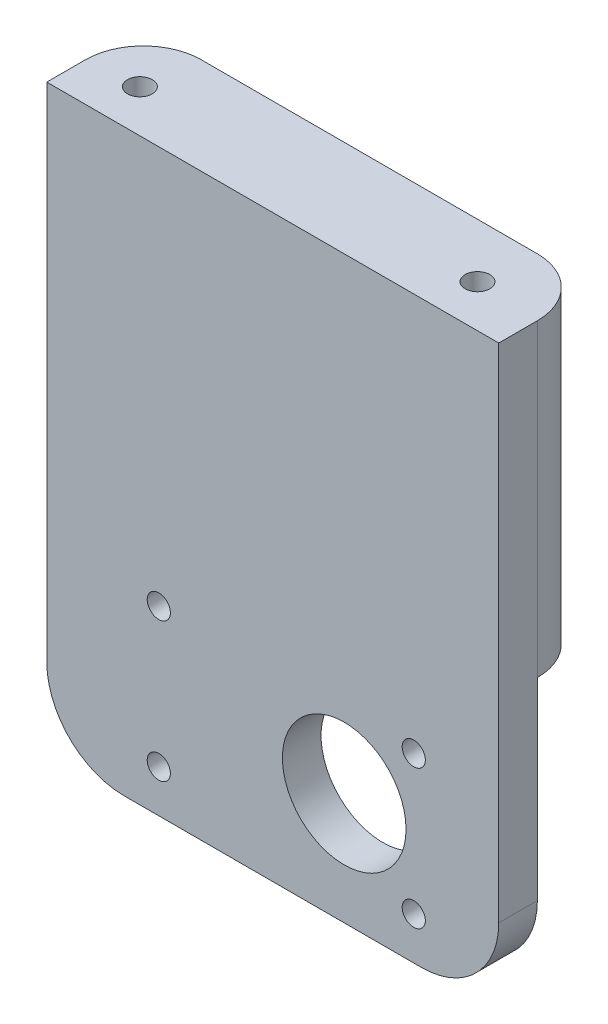
SolidWorks part; units mm, degrees
ref_plane "Front Plane" through (0, 0, 0) normal (0, 0, 1) x (1, 0, 0)
ref_plane "Top Plane" through (0, 0, 0) normal (0, 1, 0) x (1, 0, 0)
ref_plane "Right Plane" through (0, 0, 0) normal (1, 0, 0) x (0, 0, -1)
sketch "Sketch1" plane through (0, 0, 0) normal (0, 0, 1) x (1, 0, 0)
  line L5 (-24, 9) -> (9, 9) construction
  line L11 (-24, 9) -> (-24, -9) construction
  line L12 (-24, -9) -> (9, -9) construction
  line L13 (20, 60.5) -> (-38.5, 60.5)
  line L14 (20, 60.5) -> (20, -14.5)
  line L15 (20, -14.5) -> (-38.5, -14.5)
  line L16 (-38.5, 60.5) -> (-38.5, -14.5)
  line L17 (20, 60.5) -> (-38.5, -14.5) construction
  line L18 (20, -14.5) -> (-38.5, 60.5) construction
  line L23 (9, 9) -> (9, -9) construction
  line L25 (-24, 9) -> (9, -9) construction
  line L26 (-24, -9) -> (9, 9) construction
  circle A0 centre (0, 0) radius 8
  circle A1 centre (-24, -9) radius 1.5
  circle A2 centre (9, -9) radius 1.5
  circle A3 centre (9, 9) radius 1.5
  circle A4 centre (-24, 9) radius 1.5
  point P3 (-7.5, 0)
  point P9 (9, 0)
  point P10 (0, 0)
  point P11 (0, 0)
  dimension "D4" = 16
  dimension "D11" = 75
  dimension "D7" = 3
  dimension "D1" = 20
  dimension "D2" = 9
  dimension "D3" = 18
  dimension "D5" = 33
  dimension "D6" = 60.5
  dimension "D8" = 58.5
  dimension "D9" = 2
  dimension "D10" = 2
extrude "Boss-Extrude1" add sketch "Sketch1" along normal mid plane 5
sketch "Sketch4" plane through (0, 0, -2.5) normal (0, 0, -1) x (-1, 0, 0)
  line L0 (-20, 60.5) -> (-20, -14.5) construction
  line L1 (38.5, 60.5) -> (-20, 60.5)
  line L2 (38.5, 60.5) -> (38.5, 20.5)
  line L3 (38.5, 20.5) -> (-20, 20.5)
  line L4 (-20, 60.5) -> (-20, 20.5)
  dimension "D1" = 40
extrude "Boss-Extrude2" add sketch "Sketch4" along normal blind 7.5
hole_wizard "M3 Clearance Hole1" positions "Sketch2" profile "Sketch3" hole size "M3" standard "ISO"
sketch "Sketch2" plane through (0, 60.5, 0) normal (0, 1, 0) x (1, 0, 0)
  line L0 (20, -2.5) -> (20, 10) construction
  line L2 (20, -2.5) -> (-38.5, -2.5) construction
  line L3 (-38.5, -2.5) -> (-38.5, 10) construction
  point P0 (-31.95, 3)
  point P2 (11.75, 3)
  dimension "D1" = 6.55
  dimension "D2" = 8.25
  dimension "D3" = 5.5
sketch "Sketch3" plane through (-31.95, 60.5, -3) normal (1, 0, 0) x (0, 0, 1)
  line L0 (0, 0) -> (0, 4.9614)
  line L1 (0, 4.9614) -> (1.6, 4)
  line L2 (1.6, 4) -> (1.6, 0)
  line L5 (1.6, 0) -> (0, 0)
  line L10 (0, 4.9614) -> (-1.6, 4) construction
  line L11 (0, -6.35) -> (0, 107.95) construction
  dimension "Hole Dia." = 3.2
  dimension "Hole Depth" = 4
  dimension "Drill Angle" = 118
fillet "Fillet1" radius 10 2 edges at (-38.5, -14.5, 0) (20, -14.5, 0)
fillet "Fillet2" radius 7.5 2 edges at (-38.5, 40.5, -10) (20, 40.5, -10)
